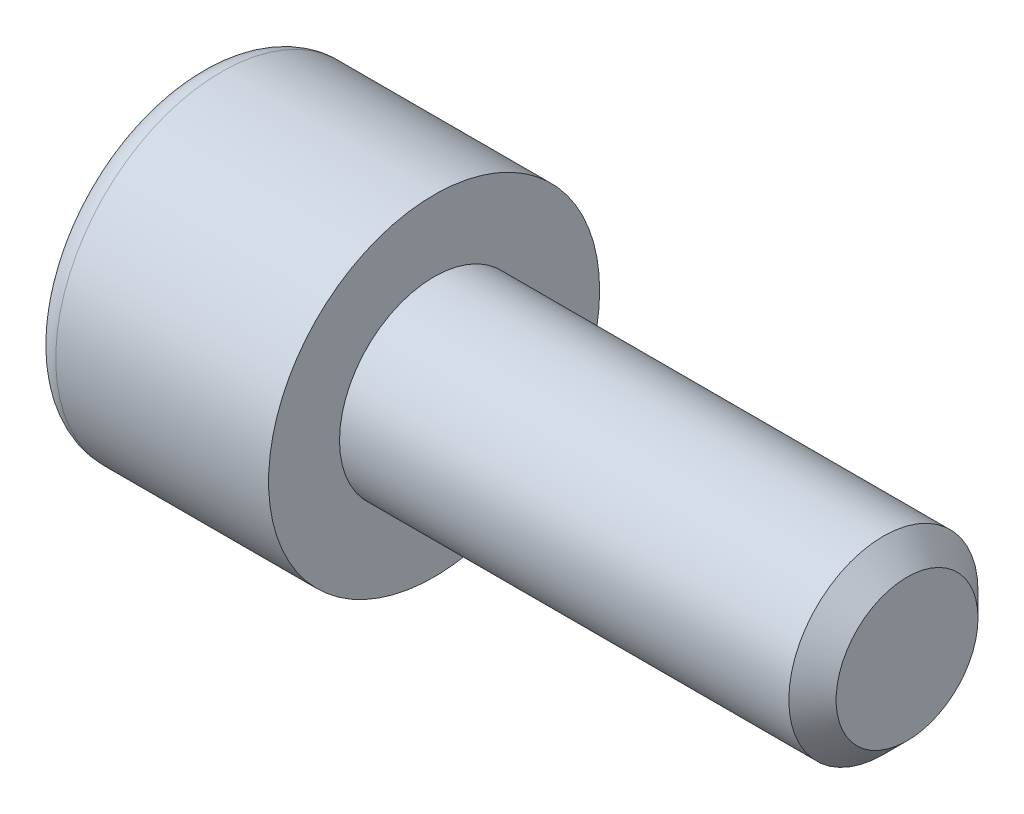
SolidWorks part; units mm, degrees
ref_plane "Спереди" through (0, 0, 0) normal (0, 0, 1) x (1, 0, 0)
ref_plane "Сверху" through (0, 0, 0) normal (0, 1, 0) x (1, 0, 0)
ref_plane "Справа" through (0, 0, 0) normal (1, 0, 0) x (0, 0, -1)
sketch "Эскиз1" plane through (0, 0, 0) normal (1, 0, 0) x (0, 0, -1)
  circle A0 centre (0, 0) radius 3.5
  dimension "D1" = 7
extrude "Вытянуть1" add sketch "Эскиз1" along normal blind 5
sketch "Эскиз2" plane through (5, 0, 0) normal (1, 0, 0) x (0, 0, -1)
  circle A0 centre (0, 0) radius 2
  dimension "D1" = 4
extrude "Вытянуть2" add sketch "Эскиз2" along normal blind 10
chamfer "Фаска1" distance 0.5 angle 45 1 edges at (15, 0, -2)
sketch "Эскиз3" plane through (0, 0, 0) normal (-1, 0, 0) x (0, 0, 1)
  line L0 (0, -1.7321) -> (0, 1.7321) construction
  line L1 (0, 1.7321) -> (-1.5, 0.866)
  line L2 (-1.5, 0.866) -> (-1.5, -0.866)
  line L3 (-1.5, -0.866) -> (0, -1.7321)
  line L4 (0, -1.7321) -> (1.5, -0.866)
  line L5 (1.5, -0.866) -> (1.5, 0.866)
  line L6 (1.5, 0.866) -> (0, 1.7321)
  circle A0 centre (0, 0) radius 1.7321
  dimension "D1" = 120
  dimension "D2" = 120
  dimension "D3" = 3
extrude "Вырез-Вытянуть1" cut sketch "Эскиз3" against normal blind 4 contours L1 L2 L3 L4 L5 L6
fillet "Скругление1" radius 1 6 edges at (4, 1.299, 0.75) (4, 0, 1.5) (4, -1.299, 0.75) (4, -1.299, -0.75) (4, 0, -1.5) (4, 1.299, -0.75)
fillet "Скругление2" radius 0.5 1 edges at (0, 0, -3.5)
